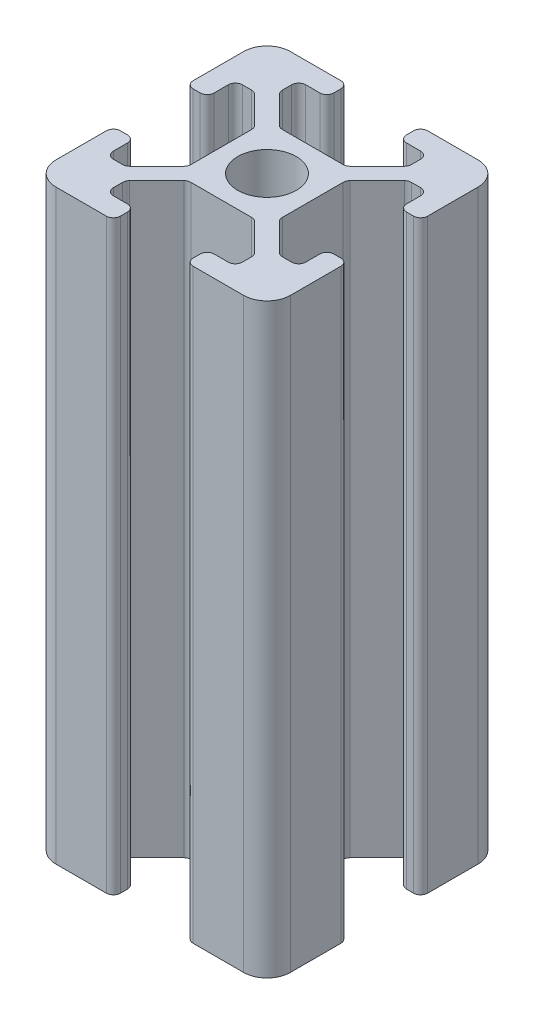
SolidWorks part; units mm, degrees
ref_plane "前视基准面" through (0, 0, 0) normal (0, 0, 1) x (1, 0, 0)
ref_plane "上视基准面" through (0, 0, 0) normal (0, 1, 0) x (1, 0, 0)
ref_plane "右视基准面" through (0, 0, 0) normal (1, 0, 0) x (0, 0, -1)
sketch "草图1" plane through (0, 0, 0) normal (0, 1, 0) x (1, 0, 0)
  line L0 (3.1, 8.8) -> (3.1, 9.4)
  line L1 (-10, -10) -> (10, -10) construction
  line L2 (-10, -10) -> (-10, 10) construction
  line L3 (-10, 10) -> (10, 10) construction
  line L4 (10, -10) -> (10, 10) construction
  line L5 (-10, -10) -> (10, 10) construction
  line L6 (-10, 10) -> (10, -10) construction
  line L7 (3.7, 10) -> (8, 10)
  line L8 (0, 10) -> (0, -10) construction
  line L9 (3.7, 8.2) -> (4.9, 8.2)
  line L10 (5.3243, 6.3849) -> (3.0151, 4.0757)
  line L11 (2.5908, 3.9) -> (0, 3.9)
  line L12 (5.5, 7.6) -> (5.5, 6.8092)
  line L13 (10, 3.7) -> (10, 8)
  line L14 (8.8, 3.1) -> (9.4, 3.1)
  line L15 (8.2, 3.7) -> (8.2, 4.9)
  line L16 (7.6, 5.5) -> (6.8092, 5.5)
  line L17 (6.3849, 5.3243) -> (4.0757, 3.0151)
  line L18 (3.9, 2.5908) -> (3.9, 0)
  line L19 (3.9, -2.5908) -> (3.9, 0)
  line L20 (2.5908, -3.9) -> (0, -3.9)
  line L21 (5.3243, -6.3849) -> (3.0151, -4.0757)
  line L22 (6.3849, -5.3243) -> (4.0757, -3.0151)
  line L23 (5.5, -7.6) -> (5.5, -6.8092)
  line L24 (3.7, -8.2) -> (4.9, -8.2)
  line L25 (3.1, -8.8) -> (3.1, -9.4)
  line L26 (3.7, -10) -> (8, -10)
  line L27 (10, -3.7) -> (10, -8)
  line L28 (8.8, -3.1) -> (9.4, -3.1)
  line L29 (8.2, -3.7) -> (8.2, -4.9)
  line L30 (7.6, -5.5) -> (6.8092, -5.5)
  line L31 (-2.5908, -3.9) -> (0, -3.9)
  line L32 (-3.9, -2.5908) -> (-3.9, 0)
  line L33 (-6.3849, -5.3243) -> (-4.0757, -3.0151)
  line L34 (-5.3243, -6.3849) -> (-3.0151, -4.0757)
  line L35 (-7.6, -5.5) -> (-6.8092, -5.5)
  line L36 (-8.2, -3.7) -> (-8.2, -4.9)
  line L37 (-8.8, -3.1) -> (-9.4, -3.1)
  line L38 (-10, -3.7) -> (-10, -8)
  line L39 (-3.7, -10) -> (-8, -10)
  line L40 (-3.1, -8.8) -> (-3.1, -9.4)
  line L41 (-3.7, -8.2) -> (-4.9, -8.2)
  line L42 (-5.5, -7.6) -> (-5.5, -6.8092)
  line L43 (-3.9, 2.5908) -> (-3.9, 0)
  line L44 (-2.5908, 3.9) -> (0, 3.9)
  line L45 (-5.3243, 6.3849) -> (-3.0151, 4.0757)
  line L46 (-6.3849, 5.3243) -> (-4.0757, 3.0151)
  line L47 (-5.5, 7.6) -> (-5.5, 6.8092)
  line L48 (-3.7, 8.2) -> (-4.9, 8.2)
  line L49 (-3.1, 8.8) -> (-3.1, 9.4)
  line L50 (-3.7, 10) -> (-8, 10)
  line L51 (-10, 3.7) -> (-10, 8)
  line L52 (-8.8, 3.1) -> (-9.4, 3.1)
  line L53 (-8.2, 3.7) -> (-8.2, 4.9)
  line L54 (-7.6, 5.5) -> (-6.8092, 5.5)
  circle A0 centre (0, 0) radius 2.5
  arc A1 (3.0151, 4.0757) -> (2.5908, 3.9) centre (2.5908, 4.5) cw
  arc A2 (5.5, 6.8092) -> (5.3243, 6.3849) centre (4.9, 6.8092) cw
  arc A3 (5.5, 7.6) -> (4.9, 8.2) centre (4.9, 7.6) ccw
  arc A4 (3.1, 8.8) -> (3.7, 8.2) centre (3.7, 8.8) ccw
  arc A5 (3.7, 10) -> (3.1, 9.4) centre (3.7, 9.4) ccw
  arc A6 (10, 3.7) -> (9.4, 3.1) centre (9.4, 3.7) cw
  arc A7 (8.8, 3.1) -> (8.2, 3.7) centre (8.8, 3.7) cw
  arc A8 (7.6, 5.5) -> (8.2, 4.9) centre (7.6, 4.9) cw
  arc A9 (6.8092, 5.5) -> (6.3849, 5.3243) centre (6.8092, 4.9) ccw
  arc A10 (4.0757, 3.0151) -> (3.9, 2.5908) centre (4.5, 2.5908) ccw
  arc A11 (10, 8) -> (8, 10) centre (8, 8) ccw
  arc A12 (3.0151, -4.0757) -> (2.5908, -3.9) centre (2.5908, -4.5) ccw
  arc A13 (4.0757, -3.0151) -> (3.9, -2.5908) centre (4.5, -2.5908) cw
  arc A14 (5.5, -6.8092) -> (5.3243, -6.3849) centre (4.9, -6.8092) ccw
  arc A15 (6.8092, -5.5) -> (6.3849, -5.3243) centre (6.8092, -4.9) cw
  arc A16 (5.5, -7.6) -> (4.9, -8.2) centre (4.9, -7.6) cw
  arc A17 (3.1, -8.8) -> (3.7, -8.2) centre (3.7, -8.8) cw
  arc A18 (3.7, -10) -> (3.1, -9.4) centre (3.7, -9.4) cw
  arc A19 (8, -10) -> (10, -8) centre (8, -8) ccw
  arc A20 (10, -3.7) -> (9.4, -3.1) centre (9.4, -3.7) ccw
  arc A21 (8.8, -3.1) -> (8.2, -3.7) centre (8.8, -3.7) ccw
  arc A22 (7.6, -5.5) -> (8.2, -4.9) centre (7.6, -4.9) ccw
  arc A23 (-4.0757, -3.0151) -> (-3.9, -2.5908) centre (-4.5, -2.5908) ccw
  arc A24 (-3.0151, -4.0757) -> (-2.5908, -3.9) centre (-2.5908, -4.5) cw
  arc A25 (-6.8092, -5.5) -> (-6.3849, -5.3243) centre (-6.8092, -4.9) ccw
  arc A26 (-5.5, -6.8092) -> (-5.3243, -6.3849) centre (-4.9, -6.8092) cw
  arc A27 (-7.6, -5.5) -> (-8.2, -4.9) centre (-7.6, -4.9) cw
  arc A28 (-8.8, -3.1) -> (-8.2, -3.7) centre (-8.8, -3.7) cw
  arc A29 (-10, -3.7) -> (-9.4, -3.1) centre (-9.4, -3.7) cw
  arc A30 (-10, -8) -> (-8, -10) centre (-8, -8) ccw
  arc A31 (-3.7, -10) -> (-3.1, -9.4) centre (-3.7, -9.4) ccw
  arc A32 (-3.1, -8.8) -> (-3.7, -8.2) centre (-3.7, -8.8) ccw
  arc A33 (-5.5, -7.6) -> (-4.9, -8.2) centre (-4.9, -7.6) ccw
  arc A34 (-3.0151, 4.0757) -> (-2.5908, 3.9) centre (-2.5908, 4.5) ccw
  arc A35 (-4.0757, 3.0151) -> (-3.9, 2.5908) centre (-4.5, 2.5908) cw
  arc A36 (-5.5, 6.8092) -> (-5.3243, 6.3849) centre (-4.9, 6.8092) ccw
  arc A37 (-6.8092, 5.5) -> (-6.3849, 5.3243) centre (-6.8092, 4.9) cw
  arc A38 (-5.5, 7.6) -> (-4.9, 8.2) centre (-4.9, 7.6) cw
  arc A39 (-3.1, 8.8) -> (-3.7, 8.2) centre (-3.7, 8.8) cw
  arc A40 (-3.7, 10) -> (-3.1, 9.4) centre (-3.7, 9.4) cw
  arc A41 (-8, 10) -> (-10, 8) centre (-8, 8) ccw
  arc A42 (-10, 3.7) -> (-9.4, 3.1) centre (-9.4, 3.7) ccw
  arc A43 (-8.8, 3.1) -> (-8.2, 3.7) centre (-8.8, 3.7) ccw
  arc A44 (-7.6, 5.5) -> (-8.2, 4.9) centre (-7.6, 4.9) ccw
  point P0 (0, 0)
  point P20 (5.5, 6.5607)
  point P25 (3.1, 8.2)
  point P28 (3.1, 10)
  point P156 (0, 0)
  dimension "D3" = 5
  dimension "D9" = 0.6
  dimension "D10" = 2
  dimension "D1" = 20
  dimension "D2" = 20
  dimension "D4" = 6.1
  dimension "D5" = 1.5
  dimension "D6" = 1.8
  dimension "D7" = 3.1
  dimension "D8" = 4.5
  dimension "D11" = 4
extrude "凸台-拉伸1" add sketch "草图1" along normal blind 50
